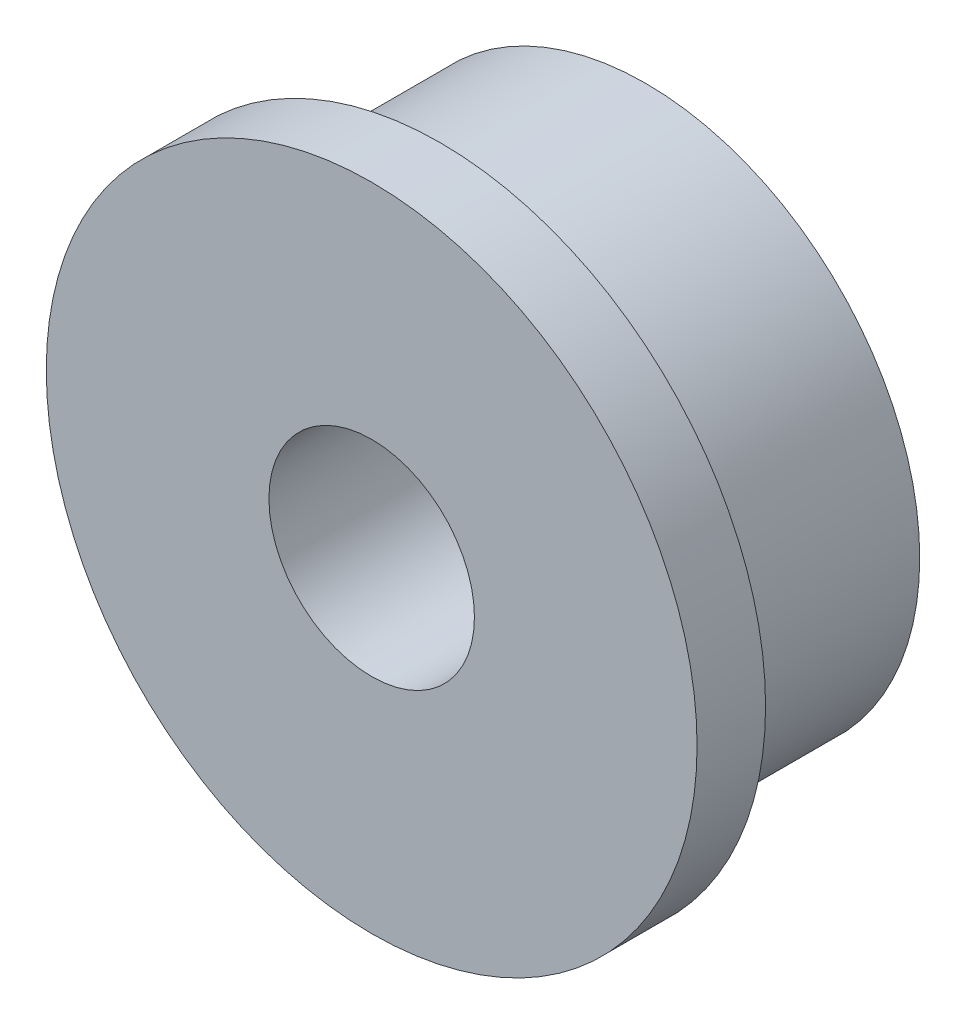
SolidWorks part; units mm, degrees
ref_plane "前视基准面" through (0, 0, 0) normal (0, 0, 1) x (1, 0, 0)
ref_plane "上视基准面" through (0, 0, 0) normal (0, 1, 0) x (1, 0, 0)
ref_plane "右视基准面" through (0, 0, 0) normal (1, 0, 0) x (0, 0, -1)
sketch "草图1" plane through (0, 0, 0) normal (0, 0, 1) x (1, 0, 0)
  circle A0 centre (0, 0) radius 1.5
  circle A1 centre (0, 0) radius 4
  dimension "D1" = 8
  dimension "D2" = 3
extrude "凸台-拉伸1" add sketch "草图1" along normal blind 3
sketch "草图2" plane through (0, 0, 3) normal (0, 0, 1) x (1, 0, 0)
  circle A0 centre (0, 0) radius 1.5
  circle A1 centre (0, 0) radius 4.75
  circle A2 centre (0, 0) radius 1.5 construction
  dimension "D1" = 9.5
extrude "凸台-拉伸2" add sketch "草图2" along normal blind 1
